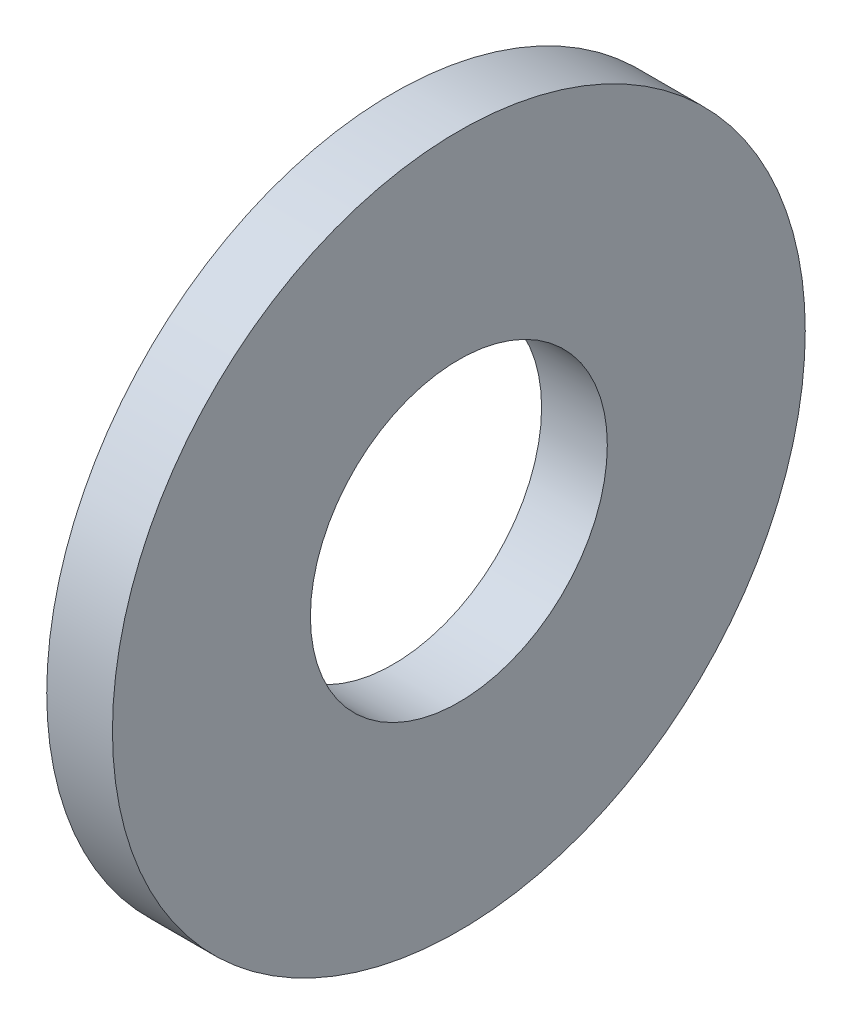
SolidWorks part; units mm, degrees
ref_plane "Plane1" through (0, 0, 0) normal (0, 0, 1) x (1, 0, 0)
ref_plane "Plane2" through (0, 0, 0) normal (0, 1, 0) x (1, 0, 0)
ref_plane "Plane3" through (0, 0, 0) normal (1, 0, 0) x (0, 0, -1)
sketch "Sketch1" plane through (0, 0, 0) normal (0, 0, 1) x (1, 0, 0)
  line L0 (-34.925, 0) -> (9.525, 0) construction
  line L1 (0, 4.7625) -> (0, 11.1125)
  line L2 (0, 11.1125) -> (-2.1082, 11.1125)
  line L3 (-2.1082, 11.1125) -> (-2.1082, 4.7625)
  line L4 (-2.1082, 4.7625) -> (0, 4.7625)
  dimension "Thickness" = 2.1082
  dimension "Inside_dia" = 9.525
  dimension "Outside_dia" = 22.225
revolve "Base-Revolve" add sketch "Sketch1" angle 360 about L0
